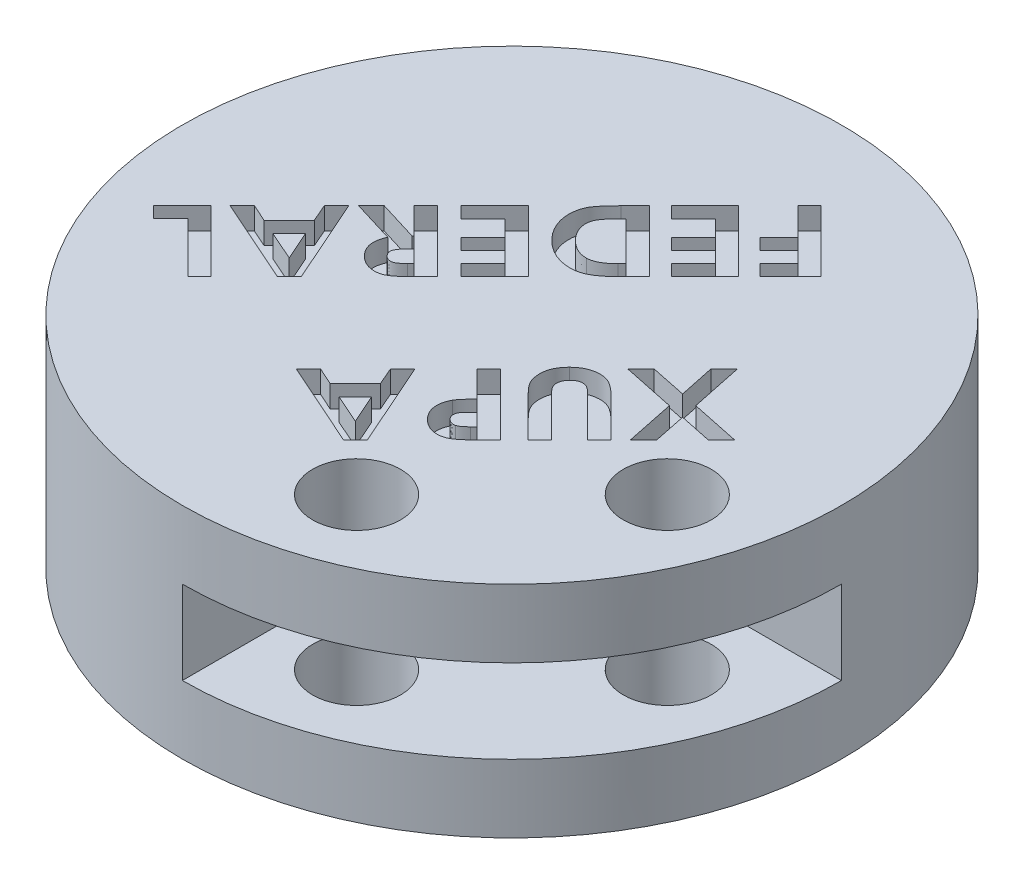
SolidWorks part; units mm, degrees
ref_plane "Plano frontal" through (0, 0, 0) normal (0, 0, 1) x (1, 0, 0)
ref_plane "Plano superior" through (0, 0, 0) normal (0, 1, 0) x (1, 0, 0)
ref_plane "Plano direito" through (0, 0, 0) normal (1, 0, 0) x (0, 0, -1)
sketch "Esboço1" plane through (0, 0, 0) normal (0, 1, 0) x (1, 0, 0)
  circle A0 centre (0, 0) radius 15
  dimension "D1" = 30
extrude "Ressalto-extrusão1" add sketch "Esboço1" along normal blind 10
ref_plane "Plano1" through (0, 5, 0) normal (0, 1, 0) x (1, 0, 0)
sketch "Esboço2" plane through (0, 5, 0) normal (0, 1, 0) x (1, 0, 0)
  line L0 (0, 0) -> (0, -15)
  line L1 (0, 0) -> (15, 0)
  arc A0 (0, -15) -> (15, 0) centre (0, 0) ccw
extrude "Corte-extrusão1" cut sketch "Esboço2" against normal mid plane 3.8
sketch "Esboço3" plane through (0, 10, 0) normal (0, 1, 0) x (1, 0, 0)
  line L0 (10.6066, 10.6066) -> (-10.6066, -10.6066) construction
  line L1 (12.5741, 8.3315) -> (-9.2306, -13.4732) construction
  line L2 (0, 0) -> (-15, 0) construction
  circle A0 centre (0, 0) radius 15 construction
  text T0 "<b>XUPA </b>\r\n<b>FEDERAL</b>" font "Century Gothic" height 4
  point P7 (0, 0)
  point P11 (1.6718, -2.5709)
  dimension "D1" = 3
  dimension "D2" = 45
extrude "Corte-extrusão2" cut sketch "Esboço3" against normal blind 1
sketch "Esboço4" plane through (0, 10, 0) normal (0, 1, 0) x (1, 0, 0)
  line L0 (0, 0) -> (7.0711, -7.0711) construction
  line L1 (0, 0) -> (13.048, 0) construction
  line L2 (10.6066, -3.5355) -> (3.5355, -10.6066) construction
  circle A1 centre (10.6066, -3.5355) radius 2
  circle A2 centre (3.5355, -10.6066) radius 2
  point P8 (7.0711, -7.0711)
  dimension "D2" = 4
  dimension "D1" = 45
  dimension "D3" = 10
  dimension "D4" = 10
extrude "Corte-extrusão3" cut sketch "Esboço4" against normal blind 10
